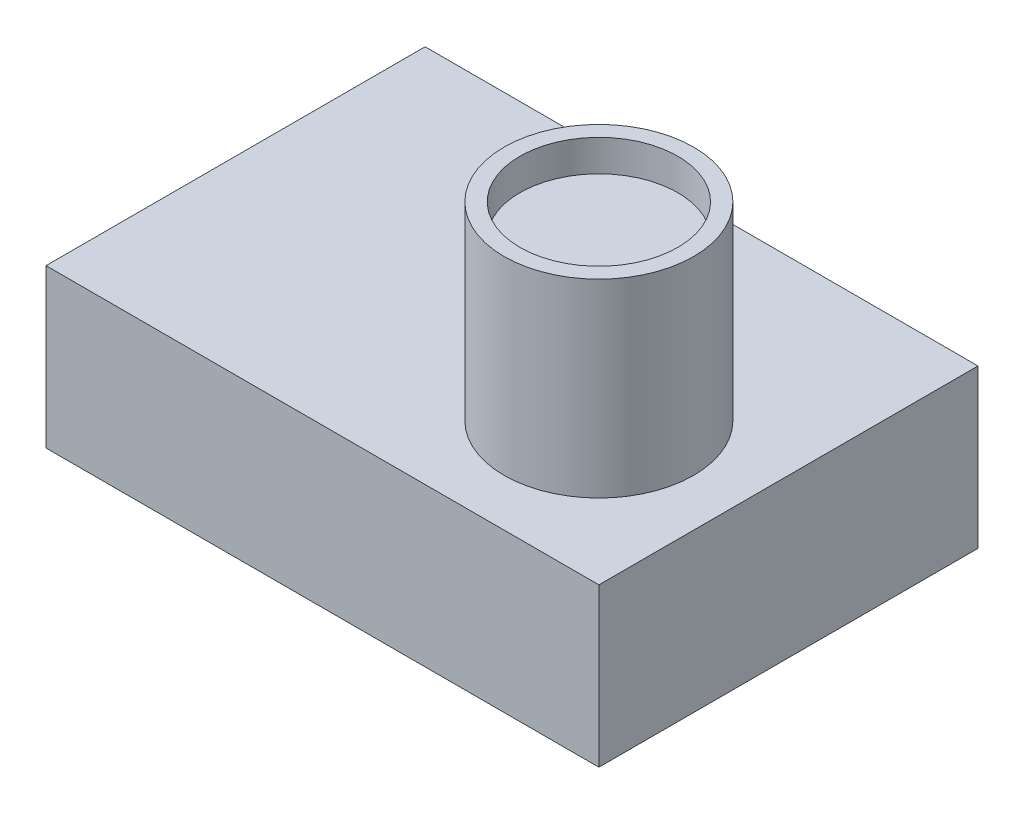
SolidWorks part; units mm, degrees
material "1060 Alloy"
ref_plane "Front Plane" through (0, 0, 0) normal (0, 0, 1) x (1, 0, 0)
ref_plane "Top Plane" through (0, 0, 0) normal (0, 1, 0) x (1, 0, 0)
ref_plane "Right Plane" through (0, 0, 0) normal (1, 0, 0) x (0, 0, -1)
sketch "Sketch2" plane through (0, 0, 0) normal (0, 1, 0) x (1, 0, 0)
  line L1 (-17.5, 12) -> (17.5, 12)
  line L2 (-17.5, 12) -> (-17.5, -12)
  line L3 (-17.5, -12) -> (17.5, -12)
  line L4 (17.5, 12) -> (17.5, -12)
  line L5 (-17.5, 12) -> (17.5, -12) construction
  line L6 (-17.5, -12) -> (17.5, 12) construction
  point P0 (0, 0)
  dimension "D1" = 35
  dimension "D2" = 24
extrude "Boss-Extrude1" add sketch "Sketch2" along normal blind 10
sketch "Sketch3" plane through (0, 10, 0) normal (0, 1, 0) x (1, 0, 0)
  line L0 (17.5, -12) -> (17.5, 12) construction
  line L1 (-17.5, -12) -> (17.5, -12) construction
  circle A0 centre (8.5, -3) radius 6
  point P2 (8.6086, -4.046)
  dimension "D1" = 12
  dimension "D2" = 9
  dimension "D3" = 9
extrude "Boss-Extrude2" add sketch "Sketch3" along normal blind 12
sketch "Sketch4" plane through (0, 22, 0) normal (0, 1, 0) x (1, 0, 0)
  circle A0 centre (8.5, -3) radius 5
  circle A1 centre (8.5, -3) radius 6 construction
  dimension "D1" = 10
extrude "Cut-Extrude2" cut sketch "Sketch4" against normal blind 2
